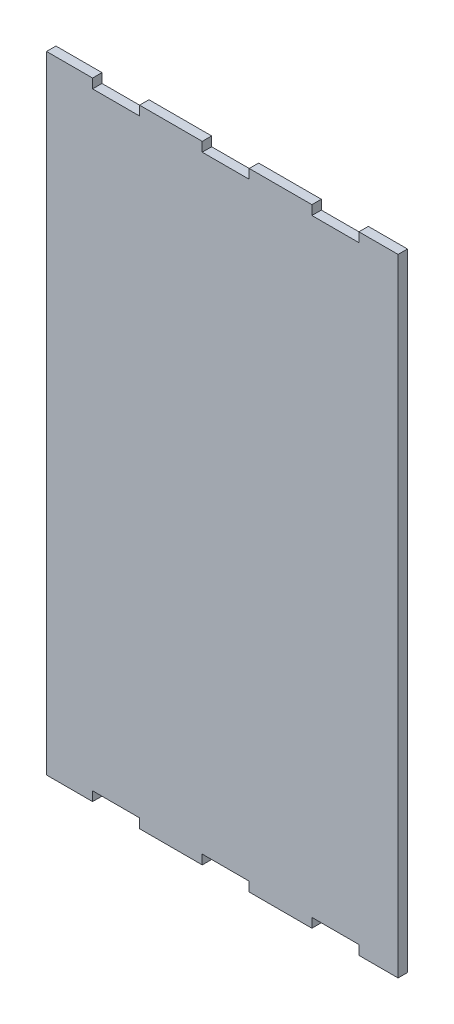
SolidWorks part; units mm, degrees
ref_plane "Front" through (0, 0, 0) normal (0, 0, 1) x (1, 0, 0)
ref_plane "Top" through (0, 0, 0) normal (0, 1, 0) x (1, 0, 0)
ref_plane "Right" through (0, 0, 0) normal (1, 0, 0) x (0, 0, -1)
sketch "草图1" plane through (0, 0, 0) normal (0, 0, 1) x (1, 0, 0)
  line L1 (0, 0) -> (110, 0)
  line L2 (0, 0) -> (0, 200)
  line L3 (0, 200) -> (110, 200)
  line L4 (110, 0) -> (110, 200)
  dimension "D1" = 200
  dimension "D2" = 110
extrude "凸台-拉伸1" add sketch "草图1" along normal blind 3
sketch "草图2" plane through (0, 0, 3) normal (0, 0, 1) x (1, 0, 0)
  line L0 (0, 0) -> (110, 0) construction
  line L1 (47.5, 0) -> (62.5, 0)
  line L2 (47.5, 0) -> (47.5, 3)
  line L3 (47.5, 3) -> (62.5, 3)
  line L4 (62.5, 0) -> (62.5, 3)
  line L6 (12.5, 0) -> (27.5, 0)
  line L7 (12.5, 0) -> (12.5, 3)
  line L8 (12.5, 3) -> (27.5, 3)
  line L9 (27.5, 0) -> (27.5, 3)
  line L10 (82.5, 3) -> (97.5, 3)
  line L11 (82.5, 3) -> (82.5, 0)
  line L12 (82.5, 0) -> (97.5, 0)
  line L13 (97.5, 3) -> (97.5, 0)
  point P6 (55, 3)
  point P7 (55, 0)
  point P16 (82.5, 1.5)
  dimension "D1" = 15
  dimension "D2" = 3
  dimension "D3" = 0
  dimension "D4" = 15
  dimension "D5" = 20
  dimension "D6" = 15
  dimension "D7" = 20
extrude "切除-拉伸1" cut sketch "草图2" against normal through all
ref_plane "基准面1" through (0, 100, 0) normal (0, -1, 0) x (-1, 0, 0)
mirror "镜向1" about plane through (0, 100, 0) normal (0, -1, 0) of "切除-拉伸1"
sketch "草图3" plane through (0, 0, 3) normal (0, 0, 1) x (1, 0, 0)
  line L0 (0, 200) -> (-2.2, 200)
  line L1 (0, 0) -> (-2.2, 0)
  line L2 (0, 0) -> (0, 200)
  line L3 (-2.2, 200) -> (-2.2, 0)
  dimension "D1" = 2.2
extrude "凸台-拉伸2" add sketch "草图3" against normal blind 3
